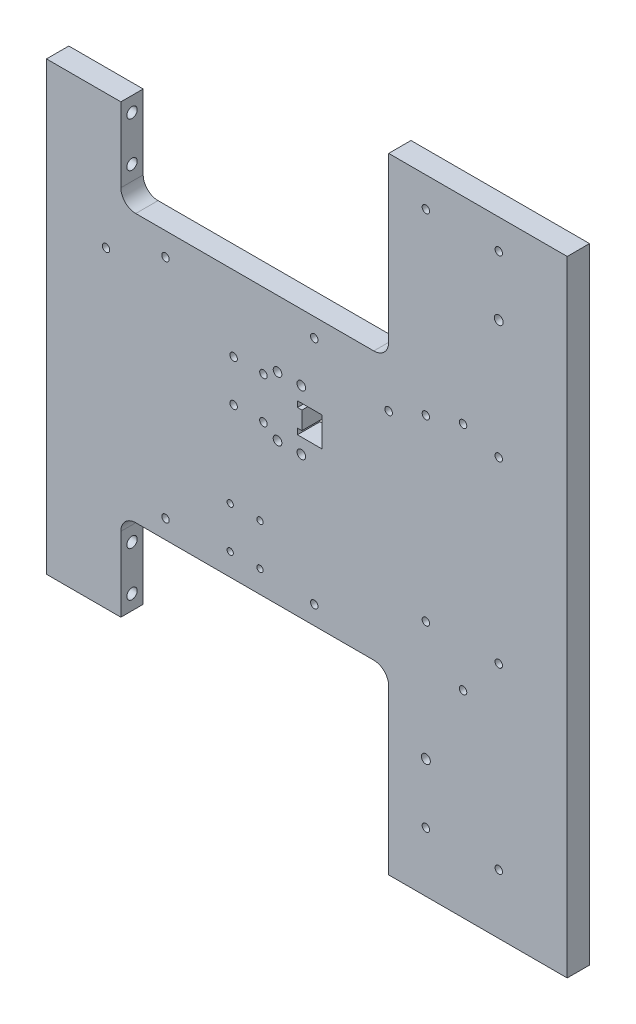
SolidWorks part; units mm, degrees
material "铝材"
ref_plane "前基準面" through (0, 0, 0) normal (0, 0, 1) x (1, 0, 0)
ref_plane "上基準面" through (0, 0, 0) normal (0, 1, 0) x (1, 0, 0)
ref_plane "右基準面" through (0, 0, 0) normal (1, 0, 0) x (0, 0, -1)
sketch "草图1" plane through (0, 0, 0) normal (0, 0, 1) x (1, 0, 0)
  line L1 (0, 0) -> (391, 0)
  line L2 (0, 0) -> (0, 180)
  line L3 (0, 180) -> (391, 180)
  line L4 (391, 0) -> (391, 180)
  dimension "D1" = 180
  dimension "D2" = 391
extrude "凸台-拉伸1" add sketch "草图1" along normal blind 15
sketch "草图3" plane through (0, 0, 15) normal (0, 0, 1) x (1, 0, 0)
  line L0 (391, 180) -> (0, 180) construction
  line L1 (173.7, 123.35) -> (183.2, 123.35)
  line L2 (173.7, 123.35) -> (173.7, 107.55)
  line L3 (173.7, 107.55) -> (183.2, 107.55)
  line L4 (183.2, 123.35) -> (183.2, 107.55)
  line L5 (0, 180) -> (0, 0) construction
  dimension "D1" = 9.5
  dimension "D2" = 15.8
  dimension "D3" = 56.65
  dimension "D4" = 173.7
extrude "切除-拉伸2" cut sketch "草图3" against normal through all
sketch "草图4" plane through (0, 0, 15) normal (0, 0, 1) x (1, 0, 0)
  line L8 (171.7, 105.55) -> (185.2, 105.55)
  line L9 (185.2, 105.55) -> (185.2, 125.35)
  line L10 (185.2, 125.35) -> (171.7, 125.35)
  line L11 (171.7, 125.35) -> (171.7, 105.55)
  line L12 (171.7, 105.55) -> (185.2, 105.55)
  line L13 (185.2, 105.55) -> (185.2, 125.35)
  line L14 (185.2, 125.35) -> (171.7, 125.35)
  line L15 (171.7, 125.35) -> (171.7, 105.55)
  dimension "D1" = 2
extrude "切除-拉伸3" cut sketch "草图4" against normal through all
sketch "草图6" plane through (0, 180, 0) normal (0, 1, 0) x (1, 0, 0)
  line L0 (391, 0) -> (0, 0) construction
  line L1 (330, 0) -> (230, 0)
  line L2 (330, 0) -> (330, -15)
  line L3 (330, -15) -> (230, -15)
  line L4 (230, 0) -> (230, -15)
  line L5 (391, -15) -> (0, -15) construction
  line L6 (0, -15) -> (0, 0) construction
  dimension "D1" = 100
  dimension "D2" = 230
extrude "凸台-拉伸2" add sketch "草图6" along normal blind 120
sketch "草图7" plane through (0, 0, 0) normal (0, -1, 0) x (1, 0, 0)
  line L0 (0, 15) -> (391, 15) construction
  line L1 (330, 15) -> (230, 15)
  line L2 (330, 15) -> (330, 0)
  line L3 (330, 0) -> (230, 0)
  line L4 (230, 15) -> (230, 0)
  line L5 (0, 0) -> (391, 0) construction
  line L6 (0, 15) -> (0, 0) construction
  dimension "D1" = 230
  dimension "D2" = 100
extrude "凸台-拉伸3" add sketch "草图7" along normal blind 120
fillet "圆角1" radius 10 2 edges
sketch "草图8" plane through (0, 0, 15) normal (0, 0, 1) x (1, 0, 0)
  line L0 (330, 0) -> (391, 0) construction
  line L1 (391, 180) -> (350, 180)
  line L2 (391, 180) -> (391, 0)
  line L3 (391, 0) -> (350, 0)
  line L4 (350, 180) -> (350, 0)
  line L5 (330, 300) -> (330, 180) construction
  dimension "D1" = 20
extrude "切除-拉伸5" cut sketch "草图8" against normal blind 120
fillet "圆角2" radius 10 2 edges
sketch "草图9" plane through (0, 180, 0) normal (0, 1, 0) x (1, 0, 0)
  line L0 (220, 0) -> (0, 0) construction
  line L1 (220, -15) -> (0, -15) construction
  line L4 (0, -15) -> (220, -15)
  line L5 (220, -15) -> (220, 0)
  line L6 (220, 0) -> (0, 0)
  line L7 (0, 0) -> (0, -15)
  line L8 (0, -15) -> (50, -15)
  line L9 (50, -15) -> (50, 0)
  line L10 (50, 0) -> (0, 0)
  line L11 (0, 0) -> (0, -15)
  dimension "D2" = 50
  dimension "D1" = 0
extrude "凸台-拉伸4" add sketch "草图9" along normal blind 60
sketch "草图10" plane through (0, 0, 0) normal (0, -1, 0) x (1, 0, 0)
  line L0 (0, 0) -> (220, 0) construction
  line L1 (0, 15) -> (220, 15) construction
  line L4 (0, 0) -> (220, 0)
  line L5 (220, 0) -> (220, 15)
  line L6 (220, 15) -> (0, 15)
  line L7 (0, 15) -> (0, 0)
  line L8 (0, 0) -> (50, 0)
  line L9 (50, 0) -> (50, 15)
  line L10 (50, 15) -> (0, 15)
  line L11 (0, 15) -> (0, 0)
  dimension "D2" = 50
  dimension "D1" = 0
extrude "凸台-拉伸5" add sketch "草图10" along normal blind 60
sketch "草图11" plane through (0, 0, 15) normal (0, 0, 1) x (1, 0, 0)
  line L1 (350, 0) -> (330, 0)
  line L2 (350, 0) -> (350, -120)
  line L3 (350, -120) -> (330, -120)
  line L4 (330, 0) -> (330, -120)
  line L5 (350, 180) -> (330, 180)
  line L6 (350, 180) -> (350, 300)
  line L7 (350, 300) -> (330, 300)
  line L8 (330, 180) -> (330, 300)
extrude "凸台-拉伸6" add sketch "草图11" against normal up to surface (15 mm away) up to face at (213, 90, 0)
fillet "圆角3" radius 10 2 edges at (50, 0, 7.5) (50, 180, 7.5)
sketch "草图12" plane through (0, 0, 0) normal (0, 0, -1) x (-1, 0, 0)
  line L0 (-171.7, 115.45) -> (-161.1013, 115.45) construction
  line L1 (-171.7, 105.55) -> (-168.7, 105.55)
  line L2 (-171.7, 105.55) -> (-171.7, 109.45)
  line L3 (-171.7, 109.45) -> (-168.7, 109.45)
  line L4 (-168.7, 105.55) -> (-168.7, 109.45)
  line L5 (-171.7, 125.35) -> (-171.7, 105.55) construction
  line L6 (-168.7, 125.35) -> (-168.7, 121.45)
  line L7 (-171.7, 121.45) -> (-168.7, 121.45)
  line L8 (-171.7, 125.35) -> (-171.7, 121.45)
  line L9 (-171.7, 125.35) -> (-168.7, 125.35)
  dimension "D1" = 3
  dimension "D2" = 12
extrude "切除-拉伸6" cut sketch "草图12" against normal through all
sketch "草图13" plane through (50, 0, 0) normal (1, 0, 0) x (0, 0, -1)
  line L0 (-7.5, -60) -> (-7.5, -10) construction
  line L1 (0, -60) -> (-15, -60) construction
  line L2 (0, -10) -> (-15, -10) construction
  line L3 (-7.5, 240) -> (-7.5, 190) construction
  line L4 (-15, 240) -> (0, 240) construction
  line L5 (-15, 190) -> (0, 190) construction
  circle A0 centre (-7.5, -50) radius 3.5
  circle A1 centre (-7.5, -20) radius 3.5
  circle A2 centre (-7.5, 230) radius 3.5
  circle A3 centre (-7.5, 200) radius 3.5
  dimension "D1" = 10
  dimension "D2" = 30
  dimension "D3" = 7
  dimension "D4" = 7
  dimension "D5" = 10
  dimension "D6" = 30
extrude "切除-拉伸7" cut sketch "草图13" against normal through all
hole_wizard "M5 螺纹孔1" positions "草图15" profile "草图14" tap size "M5" standard "ISO"
sketch "草图15" plane through (0, 0, 0) normal (0, 0, -1) x (-1, 0, 0)
  point P0 (-316, 280)
  point P1 (-316.4715, 140)
  point P4 (-316, 40)
  point P7 (-316, -100)
sketch "草图14" plane through (316, 280, 0) normal (1, 0, 0) x (0, 1, 0)
  line L0 (0, 0) -> (0, 13.6618)
  line L1 (0, 13.6618) -> (2.1, 12.4)
  line L2 (2.1, 12.4) -> (2.1, 0)
  line L5 (2.1, 0) -> (0, 0)
  line L10 (0, 13.6618) -> (-2.1, 12.4) construction
  line L11 (0, -6.35) -> (0, 107.95) construction
  dimension "螺纹孔钻头直径" = 4.2
  dimension "螺纹孔钻头深度" = 12.4
  dimension "导头角度" = 118
cosmetic thread "孔螺蚊线1" parameters "D1"=10, "D2"=5
cosmetic thread "孔螺蚊线2" parameters "D1"=10, "D2"=5
cosmetic thread "孔螺蚊线3" parameters "D1"=10, "D2"=5
cosmetic thread "孔螺蚊线4" parameters "D1"=10, "D2"=5
hole_wizard "M6 螺纹孔1" positions "草图17" profile "草图16" tap size "M6" standard "ISO"
sketch "草图17" plane through (0, 0, 0) normal (0, 0, -1) x (-1, 0, 0)
  circle A0 centre (-80, 167.5) radius 2.9 construction
  point P2 (-280, 167.5)
  point P5 (-180, 167.5)
  point P8 (-80, 164.6)
  point P14 (-280, 12.5)
  point P17 (-180, 12.5)
  point P20 (-80, 12.5)
sketch "草图16" plane through (280, 167.5, 0) normal (1, 0, 0) x (0, 1, 0)
  line L0 (0, 0) -> (0, 16.5022)
  line L1 (0, 16.5022) -> (2.5, 15)
  line L2 (2.5, 15) -> (2.5, 0)
  line L5 (2.5, 0) -> (0, 0)
  line L10 (0, 16.5022) -> (-2.5, 15) construction
  line L11 (0, -6.35) -> (0, 107.95) construction
  dimension "螺纹孔钻头直径" = 5
  dimension "螺纹孔钻头深度" = 15
  dimension "导头角度" = 118
cosmetic thread "孔螺蚊线5" parameters "D1"=12, "D2"=6
cosmetic thread "孔螺蚊线6" parameters "D1"=12, "D2"=6
cosmetic thread "孔螺蚊线7" parameters "D1"=12, "D2"=6
cosmetic thread "孔螺蚊线13" parameters "D1"=12, "D2"=6
cosmetic thread "孔螺蚊线14" parameters "D1"=12, "D2"=6
cosmetic thread "孔螺蚊线15" parameters "D1"=12, "D2"=6
hole_wizard "M6 螺纹孔2" positions "草图19" profile "草图18" tap size "M6" standard "ISO"
sketch "草图19" plane through (0, 0, 0) normal (0, 0, -1) x (-1, 0, 0)
  point P1 (-125.8, 129.45)
  point P4 (-145.8, 129.45)
  point P7 (-145.8, 101.45)
  point P10 (-125.8, 101.45)
sketch "草图18" plane through (125.8, 129.45, 0) normal (1, 0, 0) x (0, 1, 0)
  line L0 (0, 0) -> (0, 16.5022)
  line L1 (0, 16.5022) -> (2.5, 15)
  line L2 (2.5, 15) -> (2.5, 0)
  line L5 (2.5, 0) -> (0, 0)
  line L10 (0, 16.5022) -> (-2.5, 15) construction
  line L11 (0, -6.35) -> (0, 107.95) construction
  dimension "螺纹孔钻头直径" = 5
  dimension "螺纹孔钻头深度" = 15
  dimension "导头角度" = 118
cosmetic thread "孔螺蚊线9" parameters "D1"=12, "D2"=6
cosmetic thread "孔螺蚊线10" parameters "D1"=12, "D2"=6
cosmetic thread "孔螺蚊线11" parameters "D1"=12, "D2"=6
cosmetic thread "孔螺蚊线12" parameters "D1"=12, "D2"=6
hole_wizard "M5 六角凹头螺钉的柱形沉头孔1" positions "草图21" profile "草图20" counterbore size "M5" standard "ISO" end condition through all
sketch "草图21" plane through (0, 0, 0) normal (0, 0, -1) x (-1, 0, 0)
  point P0 (-171.3, 95.45)
  point P1 (-155.3, 95.45)
  point P4 (-171.3, 135.45)
  point P7 (-155.3, 135.45)
sketch "草图20" plane through (171.3, 95.45, 0) normal (1, 0, 0) x (0, 1, 0)
  line L0 (0, 0) -> (0, 15)
  line L1 (0, 15) -> (2.9, 15)
  line L3 (2.9, 15) -> (2.9, 5)
  line L4 (2.9, 5) -> (5, 5)
  line L5 (5, 5) -> (5, 0)
  line L7 (5, 0) -> (0, 0)
  line L11 (0, -6.35) -> (0, 107.95) construction
  dimension "通孔孔直径" = 5.8
  dimension "通孔孔深度" = 15
  dimension "柱形沉头孔直径" = 10
  dimension "柱形沉头孔深度" = 5
hole_wizard "M6 螺纹孔3" positions "草图23" profile "草图22" tap size "M6" standard "ISO"
sketch "草图23" plane through (0, 0, 15) normal (0, 0, 1) x (1, 0, 0)
  point P0 (304, 280)
  point P1 (255, 280)
  point P4 (255, 160)
  point P7 (304, 160)
  point P10 (304, -80)
  point P13 (255, -80)
  point P16 (255, 40)
  point P19 (304, 40)
sketch "草图22" plane through (304, 280, 15) normal (1, 0, 0) x (0, -1, 0)
  line L0 (0, 0) -> (0, 16.5022)
  line L1 (0, 16.5022) -> (2.5, 15)
  line L2 (2.5, 15) -> (2.5, 0)
  line L5 (2.5, 0) -> (0, 0)
  line L10 (0, 16.5022) -> (-2.5, 15) construction
  line L11 (0, -6.35) -> (0, 107.95) construction
  dimension "螺纹孔钻头直径" = 5
  dimension "螺纹孔钻头深度" = 15
  dimension "导头角度" = 118
cosmetic thread "孔螺蚊线16" parameters "D1"=12, "D2"=6
cosmetic thread "孔螺蚊线17" parameters "D1"=12, "D2"=6
cosmetic thread "孔螺蚊线18" parameters "D1"=12, "D2"=6
cosmetic thread "孔螺蚊线19" parameters "D1"=12, "D2"=6
cosmetic thread "孔螺蚊线20" parameters "D1"=12, "D2"=6
cosmetic thread "孔螺蚊线21" parameters "D1"=12, "D2"=6
cosmetic thread "孔螺蚊线22" parameters "D1"=12, "D2"=6
cosmetic thread "孔螺蚊线23" parameters "D1"=12, "D2"=6
hole_wizard "M6 螺纹孔4" positions "草图25" profile "草图24" tap size "M6" standard "ISO"
sketch "草图25" plane through (0, 0, 0) normal (0, 0, -1) x (-1, 0, 0)
  line L0 (-50, 240) -> (0, 240) construction
  line L1 (0, 240) -> (0, -60) construction
  point P0 (-40, 150)
  point P1 (-230, 150)
  dimension "D1" = 90
  dimension "D2" = 40
  dimension "D3" = 190
sketch "草图24" plane through (40, 150, 0) normal (1, 0, 0) x (0, 1, 0)
  line L0 (0, 0) -> (0, 16.5022)
  line L1 (0, 16.5022) -> (2.5, 15)
  line L2 (2.5, 15) -> (2.5, 0)
  line L5 (2.5, 0) -> (0, 0)
  line L10 (0, 16.5022) -> (-2.5, 15) construction
  line L11 (0, -6.35) -> (0, 107.95) construction
  dimension "螺纹孔钻头直径" = 5
  dimension "螺纹孔钻头深度" = 15
  dimension "导头角度" = 118
cosmetic thread "孔螺蚊线24" parameters "D1"=12, "D2"=6
cosmetic thread "孔螺蚊线25" parameters "D1"=12, "D2"=6
hole_wizard "M5 螺纹孔2" positions "草图27" profile "草图26" tap size "M5" standard "ISO"
sketch "草图27" plane through (0, 0, 15) normal (0, 0, 1) x (1, 0, 0)
  line L0 (60, 0) -> (220, 0) construction
  line L1 (0, 240) -> (0, -60) construction
  point P0 (123.5, 43)
  point P1 (143.5, 43)
  point P3 (143.5, 15)
  point P5 (123.5, 15)
  dimension "D1" = 15
  dimension "D2" = 28
  dimension "D3" = 20
  dimension "D4" = 123.5
sketch "草图26" plane through (123.5, 43, 15) normal (1, 0, 0) x (0, -1, 0)
  line L0 (0, 0) -> (0, 13.6618)
  line L1 (0, 13.6618) -> (2.1, 12.4)
  line L2 (2.1, 12.4) -> (2.1, 0)
  line L5 (2.1, 0) -> (0, 0)
  line L10 (0, 13.6618) -> (-2.1, 12.4) construction
  line L11 (0, -6.35) -> (0, 107.95) construction
  dimension "螺纹孔钻头直径" = 4.2
  dimension "螺纹孔钻头深度" = 12.4
  dimension "导头角度" = 118
cosmetic thread "孔螺蚊线26" parameters "D1"=10, "D2"=5
cosmetic thread "孔螺蚊线27" parameters "D1"=10, "D2"=5
cosmetic thread "孔螺蚊线28" parameters "D1"=10, "D2"=5
cosmetic thread "孔螺蚊线29" parameters "D1"=10, "D2"=5
sketch "草图28" plane through (0, 0, 15) normal (0, 0, 1) x (1, 0, 0)
  circle A0 centre (304, 240) radius 3
  circle A1 centre (255, -40) radius 3
extrude "切除-拉伸8" cut sketch "草图28" against normal through all
